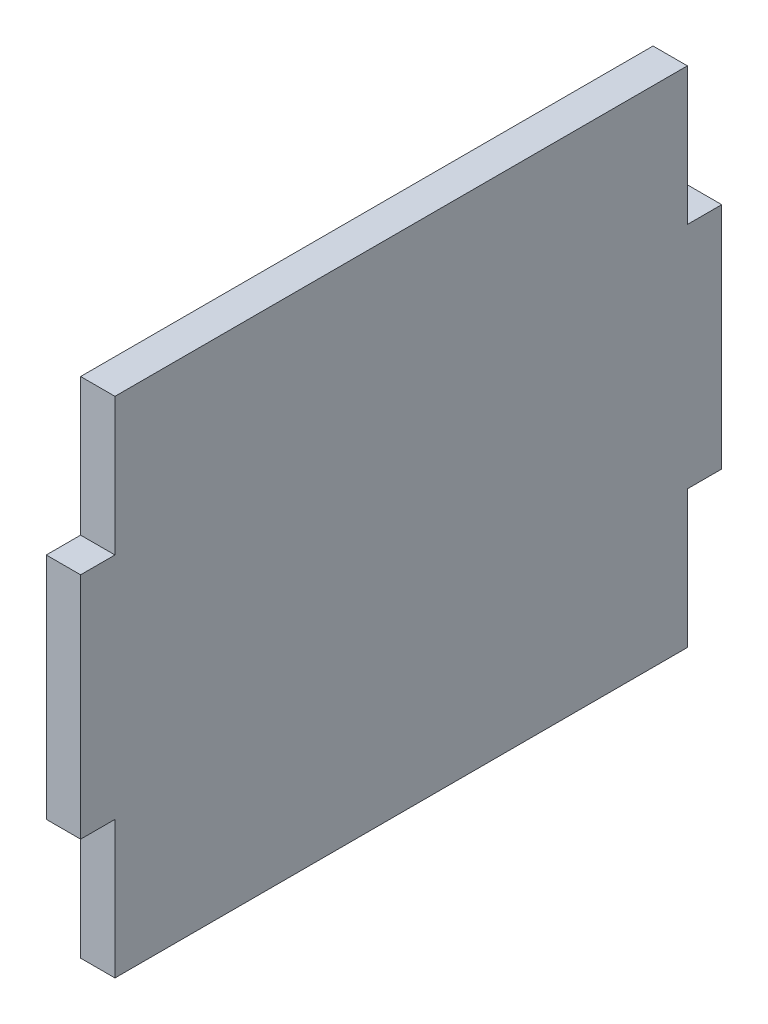
SolidWorks part; units mm, degrees
ref_plane "Front Plane" through (0, 0, 0) normal (0, 0, 1) x (1, 0, 0)
ref_plane "Top Plane" through (0, 0, 0) normal (0, 1, 0) x (1, 0, 0)
ref_plane "Right Plane" through (0, 0, 0) normal (1, 0, 0) x (0, 0, -1)
sketch "Sketch1" plane through (0, 0, 0) normal (1, 0, 0) x (0, 0, -1)
  line L0 (0, 44) -> (0, 32) construction
  line L1 (0, 0) -> (50, 0)
  line L2 (0, 0) -> (0, 12)
  line L3 (0, 44) -> (50, 44)
  line L4 (50, 0) -> (50, 12)
  line L5 (25, 44) -> (25, 0) construction
  line L6 (0, 12) -> (0, 0) construction
  line L7 (-3, 12) -> (0, 12)
  line L8 (-3, 12) -> (-3, 32)
  line L9 (-3, 32) -> (0, 32)
  line L11 (-3, 22) -> (25, 22) construction
  line L12 (53, 12) -> (50, 12)
  line L13 (0, 32) -> (0, 44)
  line L14 (53, 12) -> (53, 32)
  line L15 (53, 32) -> (50, 32)
  line L16 (50, 32) -> (50, 44)
  dimension "D1" = 50
  dimension "D2" = 44
  dimension "D3" = 20
  dimension "D4" = 3
extrude "Boss-Extrude1" add sketch "Sketch1" along normal blind 3
